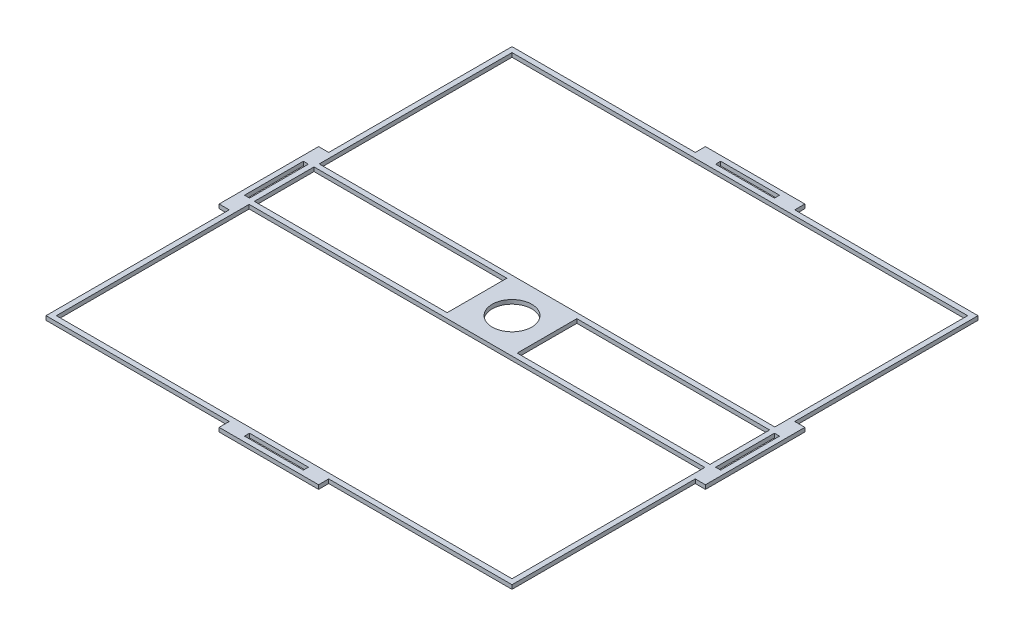
SolidWorks part; units mm, degrees
ref_plane "Front Plane" through (0, 0, 0) normal (0, 0, 1) x (1, 0, 0)
ref_plane "Top Plane" through (0, 0, 0) normal (0, 1, 0) x (1, 0, 0)
ref_plane "Right Plane" through (0, 0, 0) normal (1, 0, 0) x (0, 0, -1)
sketch "Sketch1" plane through (0, 0, 0) normal (0, 1, 0) x (1, 0, 0)
  line L0 (-55, 0) -> (55, 0) construction
  line L1 (-11.225, -11.225) -> (11.225, -11.225)
  line L2 (-11.225, -11.225) -> (-11.225, 11.225)
  line L3 (-11.225, 11.225) -> (11.225, 11.225)
  line L4 (11.225, -11.225) -> (11.225, 11.225)
  line L5 (-11.225, -11.225) -> (11.225, 11.225) construction
  line L6 (-11.225, 11.225) -> (11.225, -11.225) construction
  line L7 (-11.225, 11.225) -> (-1.725, 11.225)
  line L8 (-11.225, 11.225) -> (-11.225, 1.725)
  line L9 (-11.225, 1.725) -> (-1.725, 1.725)
  line L11 (-2.45, 11.73) -> (2.45, 11.73)
  line L12 (-11.225, -1.725) -> (-1.725, -1.725)
  line L13 (0, -55) -> (0, 55) construction
  line L14 (-11.73, -2.45) -> (-11.98, -2.45)
  line L15 (11.225, -1.725) -> (1.725, -1.725)
  line L16 (-11.73, -2.45) -> (-11.73, 2.45)
  line L17 (11.225, 1.725) -> (1.725, 1.725)
  line L18 (-1.725, 1.47) -> (-11.225, 1.47)
  line L19 (11.48, -11.48) -> (-11.48, -11.48)
  line L20 (11.48, -11.48) -> (11.48, 11.48)
  line L21 (11.48, 11.48) -> (-11.48, 11.48)
  line L22 (-11.48, -11.48) -> (-11.48, 11.48)
  line L23 (11.48, -11.48) -> (-11.48, 11.48) construction
  line L24 (11.48, 11.48) -> (-11.48, -11.48) construction
  line L25 (11.225, -1.47) -> (1.725, -1.47)
  line L26 (11.225, -1.47) -> (11.225, 1.47)
  line L27 (11.225, 1.47) -> (1.725, 1.47)
  line L28 (-11.225, -1.47) -> (-11.225, 1.47)
  line L29 (11.225, -1.47) -> (-11.225, 1.47) construction
  line L30 (11.225, 1.47) -> (-11.225, -1.47) construction
  line L31 (-1.225, -11.225) -> (1.225, -11.225)
  line L33 (-1.225, 11.225) -> (1.225, 11.225)
  line L35 (-11.73, 2.45) -> (-11.98, 2.45)
  line L36 (-11.98, -2.45) -> (-11.98, 2.45)
  line L38 (-1.725, -1.47) -> (-11.225, -1.47)
  line L40 (-11.48, 0) -> (-15.585, 0) construction
  line L41 (1.725, 1.725) -> (-1.725, 1.725)
  line L42 (1.725, 1.725) -> (1.725, -1.725)
  line L43 (1.725, -1.725) -> (-1.725, -1.725)
  line L44 (-1.725, 1.725) -> (-1.725, -1.725)
  line L45 (1.725, 1.725) -> (-1.725, -1.725) construction
  line L46 (1.725, -1.725) -> (-1.725, 1.725) construction
  line L47 (-11.48, -2.45) -> (-11.73, -2.45)
  line L48 (-11.48, 1.45) -> (-11.73, 1.45)
  line L49 (-11.48, 1.45) -> (-11.48, 2.45)
  line L50 (-11.48, 2.45) -> (-11.73, 2.45)
  line L51 (-11.73, 1.45) -> (-11.73, 2.45)
  line L52 (-11.73, -1.45) -> (-11.73, -2.45)
  line L53 (-11.48, -1.45) -> (-11.73, -1.45)
  line L54 (-11.48, -1.45) -> (-11.48, -2.45)
  line L55 (1.45, 11.48) -> (2.45, 11.48)
  line L56 (1.45, 11.48) -> (1.45, 11.73)
  line L57 (1.45, 11.73) -> (2.45, 11.73)
  line L58 (2.45, 11.48) -> (2.45, 11.73)
  line L59 (-2.45, 11.48) -> (-2.45, 11.73)
  line L60 (-1.45, 11.73) -> (-2.45, 11.73)
  line L61 (-1.45, 11.48) -> (-1.45, 11.73)
  line L62 (-1.45, 11.48) -> (-2.45, 11.48)
  line L63 (11.48, -1.45) -> (11.48, -2.45)
  line L64 (11.48, -1.45) -> (11.73, -1.45)
  line L65 (11.73, -1.45) -> (11.73, -2.45)
  line L66 (11.48, -2.45) -> (11.73, -2.45)
  line L67 (11.48, 2.45) -> (11.73, 2.45)
  line L68 (11.73, 1.45) -> (11.73, 2.45)
  line L69 (11.48, 1.45) -> (11.73, 1.45)
  line L70 (11.48, 1.45) -> (11.48, 2.45)
  line L71 (-1.45, -11.48) -> (-2.45, -11.48)
  line L72 (-1.45, -11.48) -> (-1.45, -11.73)
  line L73 (-1.45, -11.73) -> (-2.45, -11.73)
  line L74 (-2.45, -11.48) -> (-2.45, -11.73)
  line L75 (2.45, -11.48) -> (2.45, -11.73)
  line L76 (1.45, -11.73) -> (2.45, -11.73)
  line L77 (1.45, -11.48) -> (1.45, -11.73)
  line L78 (1.45, -11.48) -> (2.45, -11.48)
  line L79 (-2.45, 11.73) -> (-2.45, 11.98)
  line L80 (-2.45, 11.98) -> (2.45, 11.98)
  line L81 (2.45, 11.73) -> (2.45, 11.98)
  line L82 (11.73, 2.45) -> (11.73, -2.45)
  line L83 (11.73, 2.45) -> (11.98, 2.45)
  line L84 (11.98, 2.45) -> (11.98, -2.45)
  line L85 (11.73, -2.45) -> (11.98, -2.45)
  line L86 (2.45, -11.73) -> (-2.45, -11.73)
  line L87 (2.45, -11.73) -> (2.45, -11.98)
  line L88 (2.45, -11.98) -> (-2.45, -11.98)
  line L89 (-2.45, -11.73) -> (-2.45, -11.98)
  circle A0 centre (0, 0) radius 0.975
  point P0 (0, 0)
  point P77 (0, 0)
  point P89 (0, 0)
  dimension "D3" = 1.95
  dimension "D1" = 22.45
  dimension "D2" = 9.5
  dimension "D4" = 0.255
  dimension "D5" = 0.255
  dimension "D6" = 0.25
  dimension "D7" = 0.255
  dimension "D8" = 0.25
  dimension "D9" = 1.45
  dimension "D10" = 1
  dimension "D11" = 4
  dimension "D12" = 4
extrude "Boss-Extrude5" add sketch "Sketch1" along normal blind 0.2 contours L22 L53 L52 L47 | L51 L48 L22 L50 | L22 L19 L20 L21 L4 L1 L2 L3 | L44 L9 L2 L18 | L44 L38 L2 L12 | L17 L42 L27 L4 | L25 L42 L15 L4 | L20 L69 L68 L67 | L20 L66 L65 L64 | L41 L44 L43 L42 A0 | L73 L89 L88 L87 L76 L86 | L19 L77 L76 L75 | L19 L74 L73 L72 | L65 L85 L84 L83 L68 L82 | L21 L58 L11 L56 | L11 L81 L80 L79 | L21 L61 L11 L59 | L16 L14 L36 L35
